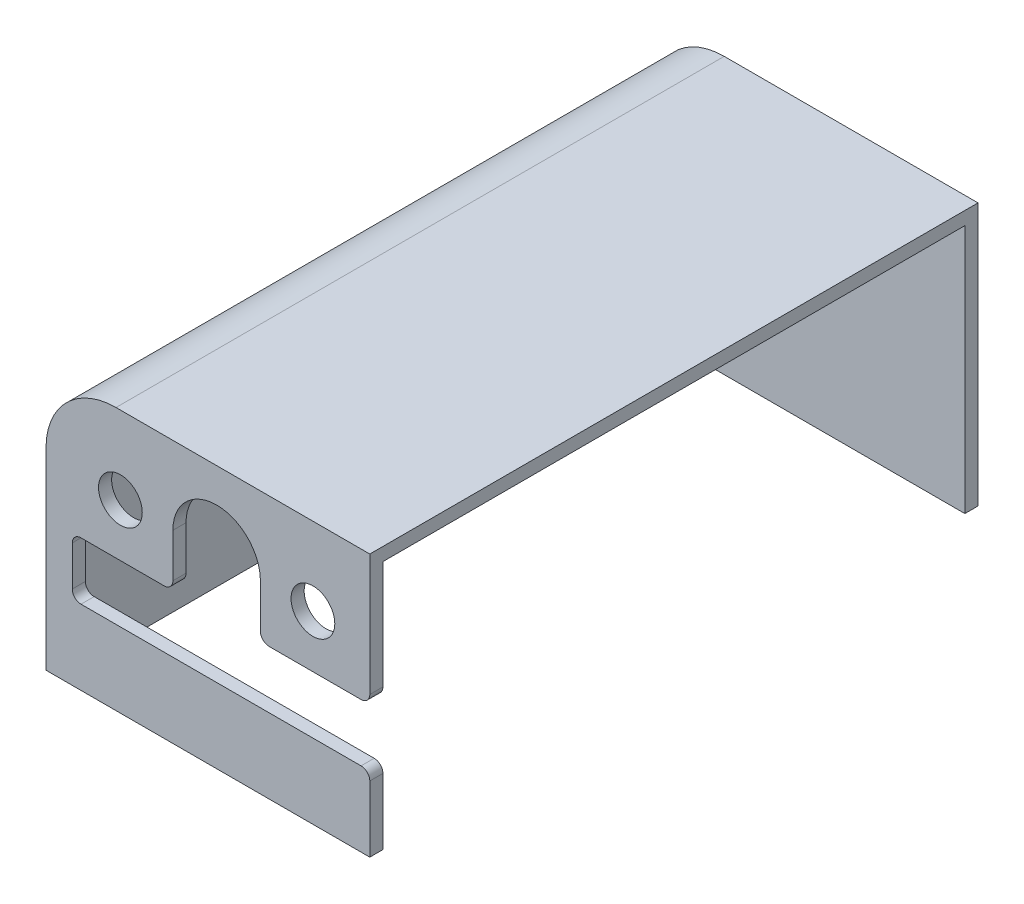
SolidWorks part; units mm, degrees
ref_plane "Front Plane" through (0, 0, 0) normal (0, 0, 1) x (1, 0, 0)
ref_plane "Top Plane" through (0, 0, 0) normal (0, 1, 0) x (1, 0, 0)
ref_plane "Right Plane" through (0, 0, 0) normal (1, 0, 0) x (0, 0, -1)
sketch "Sketch1" plane through (0, 0, 0) normal (0, 1, 0) x (1, 0, 0)
  line L0 (17.5, 35.5) -> (-18, 35.5)
  line L1 (-17.5, 35) -> (17.5, 35) construction
  line L2 (-17.5, 35) -> (-17.5, -35) construction
  line L3 (-17.5, -35) -> (17.5, -35) construction
  line L4 (17.5, 35) -> (17.5, -35) construction
  line L5 (-17.5, 35) -> (17.5, -35) construction
  line L6 (-17.5, -35) -> (17.5, 35) construction
  line L7 (-18, 35.5) -> (-18, -35.5)
  line L8 (-18, -35.5) -> (17.5, -35.5)
  line L9 (17.5, 37) -> (-19.5, 37)
  line L10 (-19.5, 37) -> (-19.5, -37)
  line L11 (-19.5, -37) -> (17.5, -37)
  line L12 (17.5, -35.5) -> (17.5, -37)
  line L13 (17.5, 37) -> (17.5, 35.5)
  point P0 (0, 0)
  dimension "D1" = 35
  dimension "D2" = 70
  dimension "D3" = 0.5
  dimension "D4" = 0.5
  dimension "D5" = 0.5
  dimension "D6" = 1.5
extrude "Boss-Extrude1" add sketch "Sketch1" along normal blind 15
sketch "Sketch2" plane through (0, 15, 0) normal (0, 1, 0) x (1, 0, 0)
  line L0 (-4, -27.5) -> (4, -27.5)
  line L1 (-19.5, -37) -> (28.4228, -37)
  line L2 (-19.5, -37) -> (-19.5, -32.5)
  line L3 (-19.5, -32.5) -> (28.4228, -32.5)
  line L4 (28.4228, -37) -> (28.4228, -32.5)
  line M5 (-19.5, 37) -> (-19.5, -37)
  line M6 (-19.5, -37) -> (17.5, -37)
  line M7 (17.5, -37) -> (17.5, -35.5)
  line M8 (17.5, -35.5) -> (-18, -35.5)
  line M9 (-18, -35.5) -> (-18, 35.5)
  dimension "D1" = 5
extrude "Cut-Extrude1" cut sketch "Sketch2" against normal through all both and the other way through all contours L1 L4 L3 M9 M8 M7 | L3 M5 M6 M7 M8 M9
sketch "Sketch3" plane through (0, 15, 0) normal (0, 1, 0) x (1, 0, 0)
  line L0 (17.5, 35.5) -> (17.5, 37) construction
  line L1 (-18, -32.5) -> (17.5, -32.5)
  line L2 (-18, -32.5) -> (-18, -31)
  line L3 (-18, -31) -> (17.5, -31)
  line L4 (17.5, -32.5) -> (17.5, -31)
  dimension "D1" = 1.5
extrude "Boss-Extrude2" add sketch "Sketch3" against normal up to vertex (15 mm away)
sketch "Sketch4" plane through (0, 15, 0) normal (0, 1, 0) x (1, 0, 0)
  line L8 (-19.5, -32.5) -> (17.5, -32.5)
  line L9 (17.5, -32.5) -> (17.5, -31)
  line L10 (17.5, -31) -> (-18, -31)
  line L11 (-18, -31) -> (-18, 35.5)
  line L12 (-18, 35.5) -> (17.5, 35.5)
  line L13 (17.5, 35.5) -> (17.5, 37)
  line L14 (17.5, 37) -> (-19.5, 37)
  line L15 (-19.5, 37) -> (-19.5, -32.5)
  line L16 (-19.5, -32.5) -> (17.5, -32.5)
  line L17 (17.5, -32.5) -> (17.5, -31)
  line L18 (17.5, -31) -> (-18, -31)
  line L19 (-18, -31) -> (-18, 35.5)
  line L20 (-18, 35.5) -> (17.5, 35.5)
  line L21 (17.5, 35.5) -> (17.5, 37)
  line L22 (17.5, 37) -> (-19.5, 37)
  line L23 (-19.5, 37) -> (-19.5, -32.5)
  dimension "D1" = 0
extrude "Boss-Extrude3" add sketch "Sketch4" along normal blind 13.5
sketch "Sketch5" plane through (0, 28.5, 0) normal (0, 1, 0) x (1, 0, 0)
  line L1 (17.5, 37) -> (-19.5, 37)
  line L2 (17.5, 37) -> (17.5, -32.5)
  line L3 (17.5, -32.5) -> (-19.5, -32.5)
  line L4 (-19.5, 37) -> (-19.5, -32.5)
extrude "Boss-Extrude4" add sketch "Sketch5" along normal blind 1.5
fillet "Fillet1" radius 8 2 edges at (-18, 28.5, -2.25) (-19.5, 30, -2.25)
sketch "Sketch6" plane through (0, 0, 32.5) normal (0, 0, 1) x (1, 0, 0)
  line L0 (17.5, 0) -> (17.5, 30) construction
  line L5 (-16.5, 15.1) -> (17.5, 15.1)
  line L6 (-16.5, 15.1) -> (-16.5, 10.1)
  line L8 (17.5, 15.1) -> (17.5, 10.1)
  line L9 (-16.5, 15.1) -> (17.5, 10.1) construction
  line L10 (0.5, 12.6) -> (17.5, 15.1) construction
  line L11 (-19.5, 0) -> (-19.5, 22) construction
  line L12 (-12.5, 12.6) -> (12.5, 12.6) construction
  line L13 (5, 15.1) -> (5, 21.1)
  line L14 (-5, 21.1) -> (-5, 15.1)
  line L15 (-11, 21.1) -> (11, 21.1) construction
  line L16 (-16.5, 10.1) -> (-16.5, 8.5372)
  line L17 (-16.5, 8.5372) -> (17.5, 8.5372)
  line L18 (17.5, 8.5372) -> (17.5, 10.1)
  arc A0 (5, 21.1) -> (-5, 21.1) centre (0, 21.1) ccw
  circle A1 centre (-11, 21.1) radius 2.5
  circle A2 centre (11, 21.1) radius 2.5
  point P0 (0.5, 12.6)
  point P23 (0, 21.1)
  dimension "D3" = 5
  dimension "D5" = 5
  dimension "D1" = 3
  dimension "D2" = 5
  dimension "D4" = 6
  dimension "D6" = 22
extrude "Cut-Extrude2" cut sketch "Sketch6" against normal blind 1.5
fillet "Fillet2" radius 1 6 edges at (17.5, 15.1, 31.75) (-16.5, 15.1, 31.75) (5, 15.1, 31.75) (-5, 15.1, 31.75) (17.5, 8.5372, 31.75) (-16.5, 8.5372, 31.75)
sketch "Sketch7" plane through (-19.5, 0, 0) normal (-1, 0, 0) x (0, 0, 1)
  circle A0 centre (25, 1.5) radius 0.75
  circle A1 centre (0, 1.5) radius 0.75
  circle A2 centre (-25, 1.5) radius 0.75
extrude "Cut-Extrude3" cut sketch "Sketch7" against normal through all both and the other way through all
